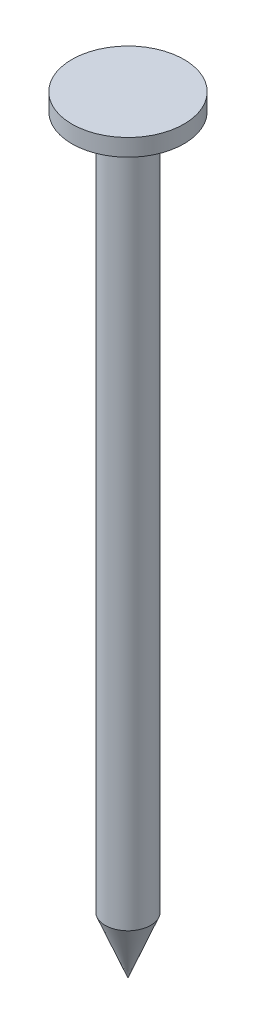
SolidWorks part; units mm, degrees
ref_plane "Front Plane" through (0, 0, 0) normal (0, 0, 1) x (1, 0, 0)
ref_plane "Top Plane" through (0, 0, 0) normal (0, 1, 0) x (1, 0, 0)
ref_plane "Right Plane" through (0, 0, 0) normal (1, 0, 0) x (0, 0, -1)
sketch "Sketch1" plane through (0, 0, 0) normal (0, 1, 0) x (1, 0, 0)
  circle A0 centre (0, 0) radius 0.6
  dimension "D1" = 1.2
extrude "Boss-Extrude1" add sketch "Sketch1" along normal blind 18.25
sketch "Sketch2" plane through (0, 18.25, 0) normal (0, 1, 0) x (1, 0, 0)
  circle A0 centre (0, 0) radius 1.475
  dimension "D1" = 2.95
extrude "Boss-Extrude2" add sketch "Sketch2" along normal blind 0.45
sketch "Sketch4" plane through (0, 0, 0) normal (1, 0, 0) x (0, 0, -1)
  line L0 (0, 0) -> (0, -1.5)
  line L1 (0.6, 0) -> (0, -1.5)
  line L2 (0.6, 0) -> (0, 0)
  dimension "D1" = 1.5
revolve "Revolve1" add sketch "Sketch4" angle 360 about L0
